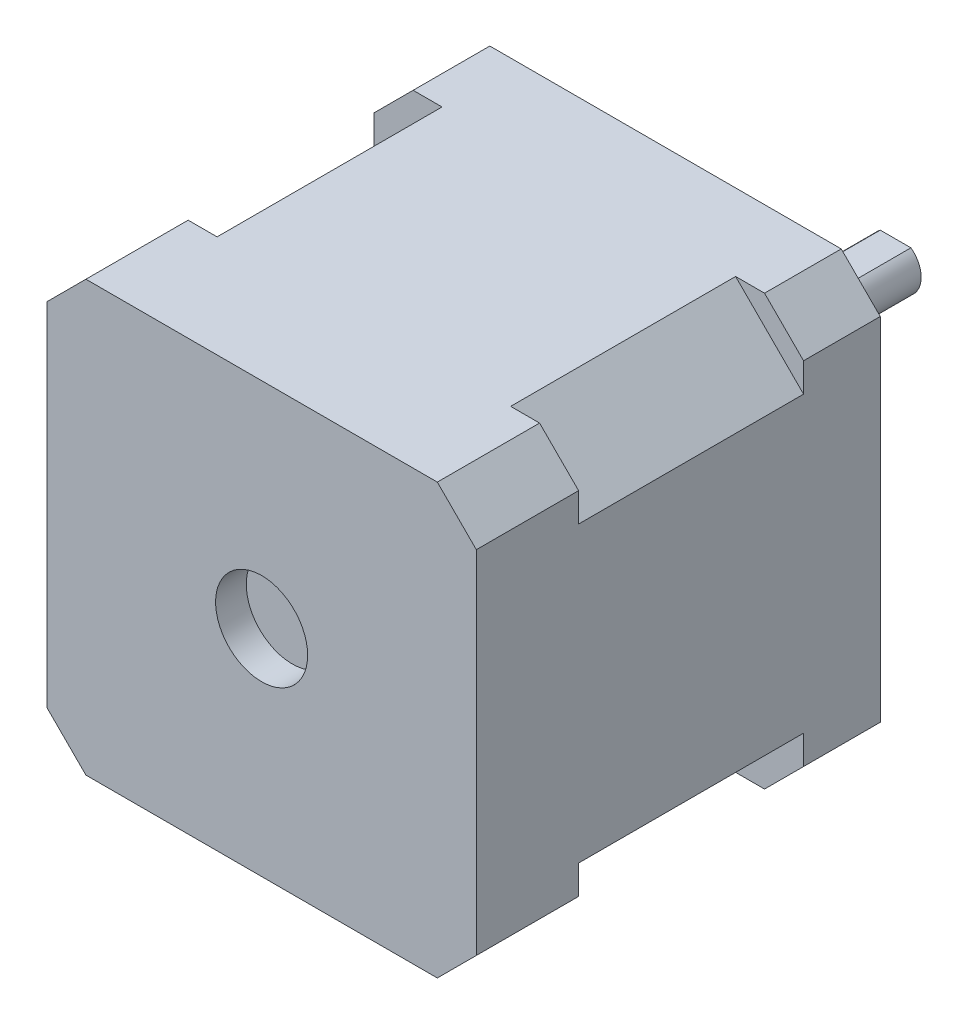
SolidWorks part; units mm, degrees
ref_plane "前视基准面" through (0, 0, 0) normal (0, 0, 1) x (1, 0, 0)
ref_plane "上视基准面" through (0, 0, 0) normal (0, 1, 0) x (1, 0, 0)
ref_plane "右视基准面" through (0, 0, 0) normal (1, 0, 0) x (0, 0, -1)
sketch "草图1" plane through (0, 0, 0) normal (0, 0, 1) x (1, 0, 0)
  line L3 (-17.1838, 21) -> (17.1838, 21)
  line L6 (21, 17.1838) -> (17.1838, 21)
  line L7 (-21, 17.1838) -> (-17.1838, 21)
  line L9 (-17.1838, -21) -> (-21, -17.1838)
  line L10 (-21, 17.1838) -> (-21, -17.1838)
  line L11 (17.1838, -21) -> (-17.1838, -21)
  line L12 (17.1838, -21) -> (21, -17.1838)
  line L13 (21, -17.1838) -> (21, 17.1838)
  point P0 (0, 0)
extrude "凸台-拉伸1" add sketch "草图1" along normal blind 39.5
sketch "草图2" plane through (0, 0, 0) normal (0, 0, -1) x (-1, 0, 0)
  circle A0 centre (0, 0) radius 11
extrude "凸台-拉伸2" add sketch "草图2" along normal blind 2
sketch "草图3" plane through (0, 0, -2) normal (0, 0, -1) x (-1, 0, 0)
  circle A0 centre (0, 0) radius 2.5
extrude "凸台-拉伸3" add sketch "草图3" along normal blind 20.5
sketch "草图4" plane through (0, 0, 0) normal (0, 0, -1) x (-1, 0, 0)
  circle A0 centre (-15.5, -15.5) radius 1.5
  circle A1 centre (-15.5, 15.5) radius 1.5
  circle A2 centre (15.5, 15.5) radius 1.5
  circle A3 centre (15.5, -15.5) radius 1.5
  point P0 (0, 0)
  point P16 (0, 0)
  dimension "D1" = 4
extrude "切除-拉伸1" cut sketch "草图4" against normal blind 5
sketch "草图5" plane through (0, 0, -22.5) normal (0, 0, -1) x (-1, 0, 0)
  line L2 (1.5, 2) -> (-1.5, 2)
  circle A0 centre (0, 0) radius 2.5 construction
  arc A2 (1.5, 2) -> (-1.5, 2) centre (0, 0) ccw
extrude "切除-拉伸2" cut sketch "草图5" against normal blind 18
sketch "草图6" plane through (0, 0, 39.5) normal (0, 0, 1) x (1, 0, 0)
  circle A0 centre (0, 0) radius 4.5
extrude "切除-拉伸3" cut sketch "草图6" against normal blind 3
sketch "草图7" plane through (0, 0, -2) normal (0, 0, -1) x (-1, 0, 0)
  circle A0 centre (0, 0) radius 4.5
  circle A1 centre (0, 0) radius 2.5
extrude "切除-拉伸4" cut sketch "草图7" against normal blind 3
ref_plane "基准面1" through (0, 0, 29.5) normal (0, 0, 1) x (1, 0, 0)
sketch "草图8" plane through (0, 0, 29.5) normal (0, 0, 1) x (1, 0, 0)
  line L2 (21, -14.3553) -> (21, 14.3553)
  line L3 (14.3553, 21) -> (21, 14.3553)
  line L4 (14.3553, -21) -> (21, -14.3553)
  line L6 (14.3553, -21) -> (-14.3553, -21)
  line L7 (-21, -14.3553) -> (-14.3553, -21)
  line L8 (-21, 14.3553) -> (-21, -14.3553)
  line L9 (-21, 14.3553) -> (-14.3553, 21)
  line L10 (-14.3553, 21) -> (14.3553, 21)
  line L12 (-30.9006, -30.109) -> (30.9006, -30.109)
  line L13 (-30.9006, -30.109) -> (-30.9006, 30.109)
  line L14 (-30.9006, 30.109) -> (30.9006, 30.109)
  line L15 (30.9006, -30.109) -> (30.9006, 30.109)
  line L16 (-30.9006, -30.109) -> (30.9006, 30.109) construction
  line L17 (-30.9006, 30.109) -> (30.9006, -30.109) construction
  point P1 (0, 0)
extrude "切除-拉伸5" cut sketch "草图8" against normal blind 22
